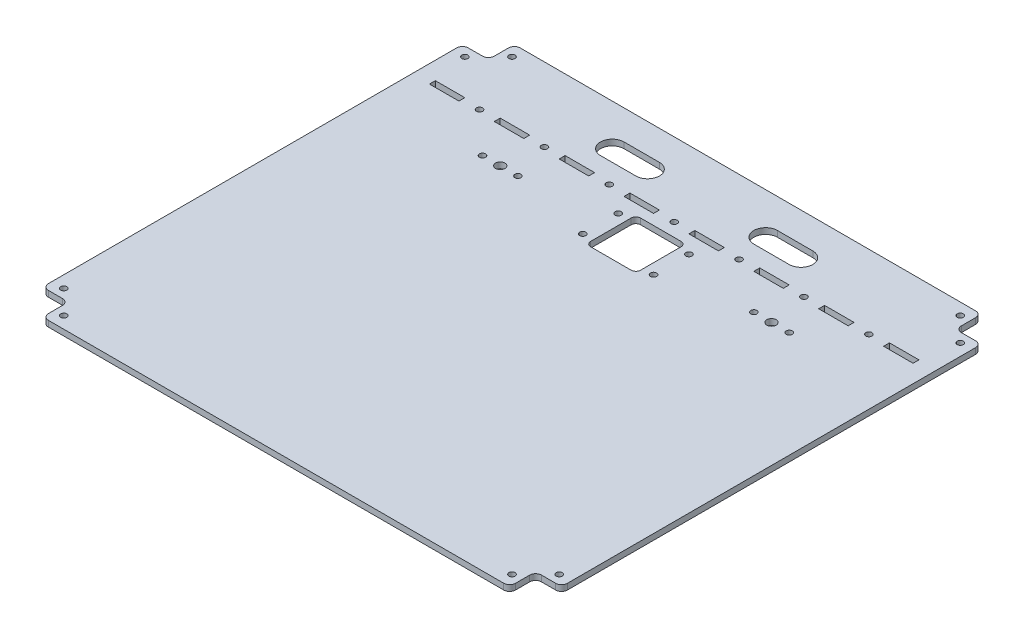
SolidWorks part; units mm, degrees
material "Acrylic (Medium-high impact)"
ref_plane "Plano frontal" through (0, 0, 0) normal (0, 0, 1) x (1, 0, 0)
ref_plane "Plano superior" through (0, 0, 0) normal (0, 1, 0) x (1, 0, 0)
ref_plane "Plano direito" through (0, 0, 0) normal (1, 0, 0) x (0, 0, -1)
sketch "Sketch1" plane through (0, 0, 0) normal (0, 1, 0) x (1, 0, 0)
  line L1 (-220, 200) -> (220, 200)
  line L2 (-220, 200) -> (-220, -200)
  line L3 (-220, -200) -> (220, -200)
  line L4 (220, 200) -> (220, -200)
  line L5 (-220, 200) -> (220, -200) construction
  line L6 (-220, -200) -> (220, 200) construction
  point P0 (0, 0)
  dimension "D1" = 440
  dimension "D2" = 400
extrude "Boss-Extrude1" add sketch "Sketch1" along normal mid plane 5
sketch "Sketch2" plane through (0, 2.5, 0) normal (0, 1, 0) x (1, 0, 0)
  line L1 (220, 200) -> (198, 200)
  line L2 (220, 200) -> (220, 178)
  line L3 (220, 178) -> (198, 178)
  line L4 (198, 200) -> (198, 178)
  dimension "D1" = 22
  dimension "D2" = 22
extrude "Cut-Extrude1" cut sketch "Sketch2" against normal up to surface (5 mm away) up to face at (0, -2.5, 0)
sketch "Sketch3" plane through (0, 2.5, 0) normal (0, 1, 0) x (1, 0, 0)
  line L0 (198, 200) -> (-220, 200) construction
  line L1 (220, -200) -> (220, 178) construction
  line L2 (198, 200) -> (198, 178) construction
  line L3 (198, 178) -> (220, 178) construction
  circle A0 centre (190, 190) radius 2.6
  circle A1 centre (210, 170) radius 2.6
  dimension "D1" = 5.2
  dimension "D2" = 5.2
  dimension "D3" = 10
  dimension "D4" = 10
  dimension "D5" = 8
  dimension "D6" = 8
extrude "Cut-Extrude2" cut sketch "Sketch3" against normal up to surface (5 mm away) up to face at (66, -2.5, -59.3333)
mirror "Mirror1" about plane through (0, 0, 0) normal (1, 0, 0) of "Cut-Extrude2", "Cut-Extrude1"
mirror "Mirror2" about plane through (0, 0, 0) normal (0, 0, 1) of "Mirror1", "Cut-Extrude1", "Cut-Extrude2"
fillet "Fillet1" radius 5 12 edges at (220, 0, 178) (220, 0, -178) (198, 0, -178) (198, 0, -200) (-198, 0, -200) (-198, 0, -178) (-220, 0, -178) (-220, 0, 178) (-198, 0, 178) (198, 0, 200) (198, 0, 178) (-198, 0, 200)
sketch "Sketch4" plane through (0, 2.5, 0) normal (0, 1, 0) x (1, 0, 0)
  line L0 (-220, 173) -> (-220, -173) construction
  line L1 (-205, 140) -> (-180, 140)
  line L2 (-205, 140) -> (-205, 135)
  line L3 (-205, 135) -> (-180, 135)
  line L4 (-180, 140) -> (-180, 135)
  line L5 (193, 200) -> (-193, 200) construction
  dimension "D1" = 15
  dimension "D2" = 5
  dimension "D3" = 25
  dimension "D4" = 60
extrude "Cut-Extrude3" cut sketch "Sketch4" against normal up to surface (5 mm away) up to face at (210, -2.5, 172.6)
pattern_linear "LPattern1" count 8 spacing 55 along (1, 0, 0) of "Cut-Extrude3"
sketch "Sketch5" plane through (0, 2.5, 0) normal (0, 1, 0) x (1, 0, 0)
  line L0 (-180, 137.5) -> (-150, 137.5) construction
  line L1 (-180, 135) -> (-180, 140) construction
  line L2 (-150, 140) -> (-150, 135) construction
  circle A0 centre (-165, 137.5) radius 2.6
  dimension "D1" = 5.2
extrude "Cut-Extrude4" cut sketch "Sketch5" against normal up to surface (5 mm away) up to face at (-82.5, -2.5, -137.5)
pattern_linear "LPattern2" count 7 spacing 55 along (1, 0, 0) of "Cut-Extrude4"
sketch "Sketch6" plane through (0, 2.5, 0) normal (0, 1, 0) x (1, 0, 0)
  line L0 (0, 200) -> (0, -200) construction
  line L1 (193, 200) -> (-193, 200) construction
  line L2 (-193, -200) -> (193, -200) construction
  line L3 (15, 135) -> (40, 135) construction
  line L4 (-21.15, 126.15) -> (21.15, 126.15)
  line L5 (-21.15, 126.15) -> (-21.15, 83.85)
  line L6 (-21.15, 83.85) -> (21.15, 83.85)
  line L7 (21.15, 126.15) -> (21.15, 83.85)
  line L8 (-21.15, 126.15) -> (21.15, 83.85) construction
  line L9 (-21.15, 83.85) -> (21.15, 126.15) construction
  point P6 (0, 105)
  dimension "D1" = 42.3
  dimension "D2" = 42.3
  dimension "D3" = 8.85
extrude "Cut-Extrude5" cut sketch "Sketch6" against normal up to surface (5 mm away) up to face at (-55, -2.5, -134.9)
fillet "Fillet2" radius 4 4 edges at (21.15, 0, -83.85) (-21.15, 0, -83.85) (-21.15, 0, -126.15) (21.15, 0, -126.15)
sketch "Sketch7" plane through (0, 2.5, 0) normal (0, 1, 0) x (1, 0, 0)
  line L0 (0, 126.15) -> (0, 83.85) construction
  line L1 (17.15, 126.15) -> (-17.15, 126.15) construction
  line L2 (-17.15, 83.85) -> (17.15, 83.85) construction
  line L3 (21.15, 87.85) -> (21.15, 122.15) construction
  line L4 (-21.15, 105) -> (21.15, 105) construction
  line L5 (-21.15, 122.15) -> (-21.15, 87.85) construction
  circle A0 centre (30, 120) radius 2.6
  dimension "D1" = 5.2
  dimension "D2" = 30
  dimension "D3" = 15
extrude "Cut-Extrude7" cut sketch "Sketch7" against normal up to surface (5 mm away) up to face at (0, -2.5, -105)
pattern_linear "LPattern3" count 2 spacing 60 along (-1, 0, 0) count 2 spacing 30 along (0, 0, 1) of "Cut-Extrude7"
sketch "Sketch8" plane through (0, 2.5, 0) normal (0, 1, 0) x (1, 0, 0)
  line L0 (0, 126.15) -> (0, 83.85) construction
  line L1 (17.15, 126.15) -> (-17.15, 126.15) construction
  line L2 (-17.15, 83.85) -> (17.15, 83.85) construction
  line L3 (21.15, 105) -> (-21.15, 105) construction
  line L4 (21.15, 87.85) -> (21.15, 122.15) construction
  line L5 (-21.15, 122.15) -> (-21.15, 87.85) construction
  line L6 (-150, 135) -> (-125, 135) construction
  circle A0 centre (-115, 105) radius 4
  circle A1 centre (-100, 105) radius 2.6
  circle A2 centre (-130, 105) radius 2.6
  point P18 (-115, 83.85)
  point P19 (0, 0)
  dimension "D1" = 8
  dimension "D3" = 5.2
  dimension "D4" = 5.2
  dimension "D2" = 115
  dimension "D5" = 15
  dimension "D6" = 15
  dimension "D7" = 30
extrude "Cut-Extrude8" cut sketch "Sketch8" against normal up to surface (5 mm away) up to face at (-30, -2.5, -117.4)
mirror "Mirror3" about plane through (0, 0, 0) normal (1, 0, 0) of "Cut-Extrude8"
sketch "Sketch9" plane through (0, 2.5, 0) normal (0, 1, 0) x (1, 0, 0)
  line L0 (50, 165) -> (80, 165) construction
  line L1 (50, 175) -> (80, 175)
  line L2 (50, 155) -> (80, 155)
  line L3 (193, 200) -> (-193, 200) construction
  line L4 (220, -173) -> (220, 173) construction
  arc A0 (50, 175) -> (50, 155) centre (50, 165) ccw
  arc A1 (80, 155) -> (80, 175) centre (80, 165) ccw
  point P2 (65, 165)
  dimension "D2" = 10
  dimension "D1" = 30
  dimension "D3" = 25
  dimension "D4" = 140
extrude "Cut-Extrude9" cut sketch "Sketch9" against normal up to surface (5 mm away) up to face at (100, -2.5, -102.4)
mirror "Mirror4" about plane through (0, 0, 0) normal (1, 0, 0) of "Cut-Extrude9"
equation "\"M5\"= 5.2mm"
